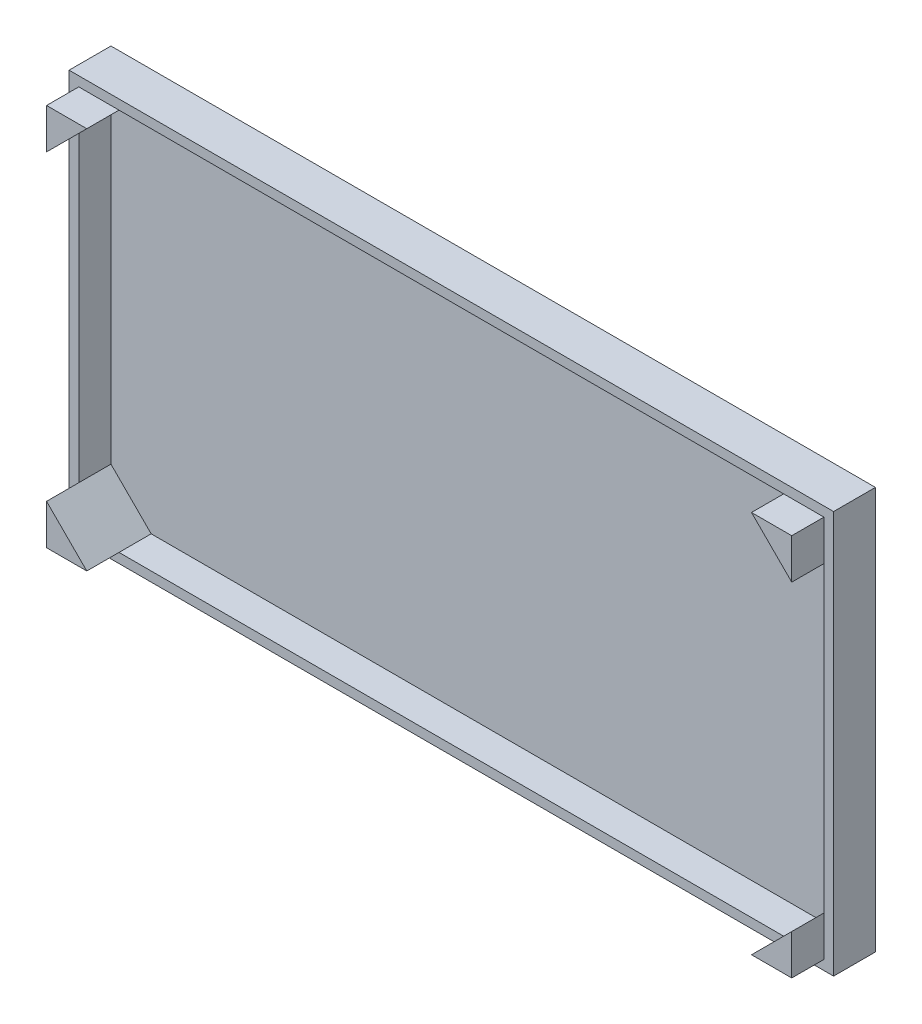
SolidWorks part; units mm, degrees
ref_plane "Přední rovina" through (0, 0, 0) normal (0, 0, 1) x (1, 0, 0)
ref_plane "Horní rovina" through (0, 0, 0) normal (0, 1, 0) x (1, 0, 0)
ref_plane "Pravá rovina" through (0, 0, 0) normal (1, 0, 0) x (0, 0, -1)
sketch "Skica1" plane through (0, 0, 0) normal (0, 0, 1) x (1, 0, 0)
  line L1 (0, 0) -> (95, 0)
  line L2 (0, 0) -> (0, 50)
  line L3 (0, 50) -> (95, 50)
  line L4 (95, 0) -> (95, 50)
  dimension "D1" = 95
  dimension "D2" = 50
extrude "Přidat vysunutím1" add sketch "Skica1" along normal blind 1.2
sketch "Skica2" plane through (0, 0, 1.2) normal (0, 0, 1) x (1, 0, 0)
  line L1 (0, 50) -> (95, 50)
  line L2 (0, 50) -> (0, 0)
  line L3 (0, 0) -> (95, 0)
  line L4 (95, 50) -> (95, 0)
  line L5 (1.2, 48.8) -> (93.8, 48.8)
  line L6 (1.2, 48.8) -> (1.2, 1.2)
  line L7 (1.2, 1.2) -> (93.8, 1.2)
  line L8 (93.8, 48.8) -> (93.8, 1.2)
  dimension "D1" = 1.2
  dimension "D2" = 1.2
  dimension "D3" = 1.2
  dimension "D4" = 1.2
extrude "Přidat vysunutím2" add sketch "Skica2" along normal blind 4
sketch "Skica3" plane through (0, 0, 1.2) normal (0, 0, 1) x (1, 0, 0)
  line L0 (1.2, 48.8) -> (6.2, 48.8)
  line L1 (93.8, 48.8) -> (1.2, 48.8) construction
  line L2 (6.2, 48.8) -> (1.2, 43.8)
  line L3 (1.2, 48.8) -> (1.2, 1.2) construction
  line L4 (1.2, 43.8) -> (1.2, 48.8)
  line L5 (93.8, 48.8) -> (93.8, 43.8)
  line L6 (93.8, 1.2) -> (93.8, 48.8) construction
  line L7 (93.8, 43.8) -> (88.8, 48.8)
  line L8 (88.8, 48.8) -> (93.8, 48.8)
  line L9 (93.8, 1.2) -> (88.8, 1.2)
  line L10 (1.2, 1.2) -> (93.8, 1.2) construction
  line L11 (88.8, 1.2) -> (93.8, 6.2)
  line L12 (93.8, 6.2) -> (93.8, 1.2)
  line L13 (1.2, 1.2) -> (1.2, 6.2)
  line L14 (1.2, 6.2) -> (6.2, 1.2)
  line L15 (6.2, 1.2) -> (1.2, 1.2)
  dimension "D1" = 5
  dimension "D2" = 5
  dimension "D3" = 5
  dimension "D4" = 5
  dimension "D5" = 5
  dimension "D6" = 5
  dimension "D7" = 5
  dimension "D8" = 5
extrude "Přidat vysunutím3" add sketch "Skica3" along normal blind 8
